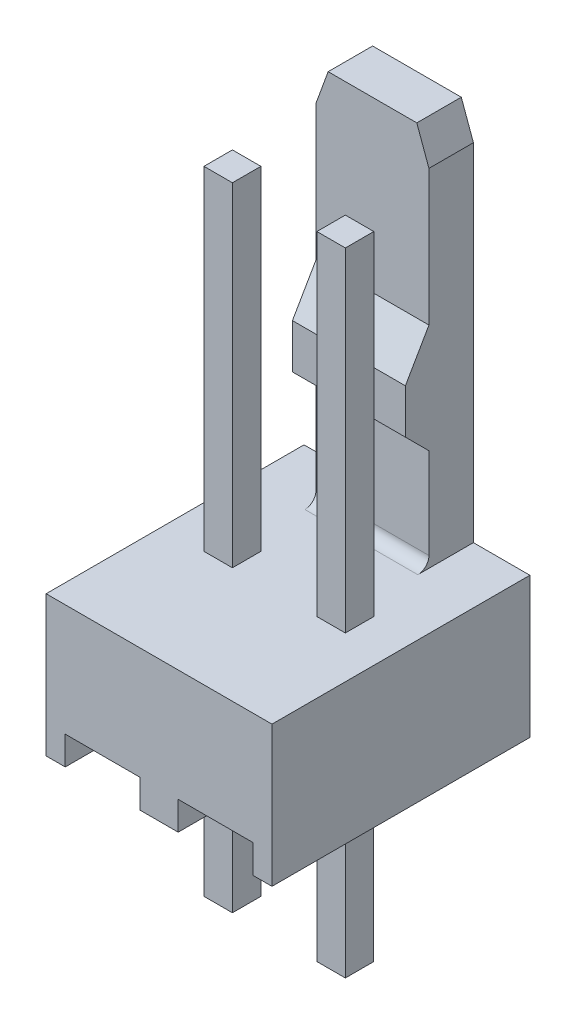
SolidWorks part; units mm, degrees
ref_plane "Front Plane" through (0, 0, 0) normal (0, 0, 1) x (1, 0, 0)
ref_plane "Top Plane" through (0, 0, 0) normal (0, 1, 0) x (1, 0, 0)
ref_plane "Right Plane" through (0, 0, 0) normal (1, 0, 0) x (0, 0, -1)
ref_plane "Plane1" through (0, -1.58, 0) normal (0, -1, 0) x (1, 0, 0)
sketch "Sketch1" plane through (0, -1.58, 0) normal (0, -1, 0) x (1, 0, 0)
  line L0 (2.54, -2.88) -> (2.54, 2.92)
  line L1 (2.54, 2.92) -> (-2.54, 2.92)
  line L2 (-2.54, 2.92) -> (-2.54, -2.88)
  line L3 (-2.54, -2.88) -> (2.54, -2.88)
extrude "Boss-Extrude1" add sketch "Sketch1" against normal blind 3.16
sketch "Sketch2" plane through (0, 1.58, 0) normal (0, 1, 0) x (-1, 0, 0)
  line L0 (1.27, -1.88) -> (1.27, -2.88)
  line L1 (1.27, -2.88) -> (-1.27, -2.88)
  line L2 (-1.27, -2.88) -> (-1.27, -1.88)
  line L3 (-1.27, -1.88) -> (1.27, -1.88)
extrude "Boss-Extrude2" add sketch "Sketch2" along normal blind 8.54
sketch "Sketch3" plane through (0, 0, -1.88) normal (0, 0, 1) x (1, 0, 0)
  line L0 (1.27, 10.12) -> (1.27, 3.87)
  line L1 (1.27, 3.87) -> (-1.27, 3.87)
  line L2 (-1.27, 3.87) -> (-1.27, 10.12)
  line L3 (-1.27, 10.12) -> (1.27, 10.12)
extrude "Boss-Extrude3" add sketch "Sketch3" along normal blind 0.53
sketch "Sketch4" plane through (0, 0, -2.88) normal (0, 0, -1) x (-1, 0, 0)
  line L0 (0.43, -1.58) -> (2.11, -1.58)
  line L1 (2.11, -1.58) -> (2.11, -0.94)
  line L2 (2.11, -0.94) -> (0.43, -0.94)
  line L3 (0.43, -0.94) -> (0.43, -1.58)
extrude "Cut-Extrude1" cut sketch "Sketch4" against normal through all
sketch "Sketch5" plane through (1.27, 0, 0) normal (1, 0, 0) x (0, 0, -1)
  line L0 (1.35, 6.318) -> (1.88, 6.318)
  line L1 (1.88, 6.318) -> (1.88, 10.12)
  line L2 (1.88, 10.12) -> (1.35, 10.12)
  line L3 (1.35, 10.12) -> (1.35, 6.318)
extrude "Cut-Extrude2" cut sketch "Sketch5" against normal through all
sketch "Sketch6" plane through (0, 0, -2.88) normal (0, 0, -1) x (-1, 0, 0)
  line L0 (-2.11, -1.58) -> (-0.43, -1.58)
  line L1 (-0.43, -1.58) -> (-0.43, -0.94)
  line L2 (-0.43, -0.94) -> (-2.11, -0.94)
  line L3 (-2.11, -0.94) -> (-2.11, -1.58)
extrude "Cut-Extrude3" cut sketch "Sketch6" against normal through all
sketch "Sketch7" plane through (0, -0.94, 0) normal (0, -1, 0) x (1, 0, 0)
  line L0 (-1.59, -0.32) -> (-1.59, 0.32)
  line L1 (-1.59, 0.32) -> (-0.95, 0.32)
  line L2 (-0.95, 0.32) -> (-0.95, -0.32)
  line L3 (-0.95, -0.32) -> (-1.59, -0.32)
extrude "Boss-Extrude4" add sketch "Sketch7" along normal blind 4.2
sketch "Sketch8" plane through (0, -0.94, 0) normal (0, -1, 0) x (1, 0, 0)
  line L0 (1.59, 0.32) -> (1.59, -0.315)
  line L1 (1.59, -0.315) -> (0.95, -0.315)
  line L2 (0.95, -0.315) -> (0.95, 0.32)
  line L3 (0.95, 0.32) -> (1.59, 0.32)
extrude "Boss-Extrude5" add sketch "Sketch8" along normal blind 4.2
sketch "Sketch9" plane through (0, 1.58, 0) normal (0, 1, 0) x (-1, 0, 0)
  line L0 (-1.59, -0.32) -> (-1.59, 0.32)
  line L1 (-1.59, 0.32) -> (-0.95, 0.32)
  line L2 (-0.95, 0.32) -> (-0.95, -0.32)
  line L3 (-0.95, -0.32) -> (-1.59, -0.32)
extrude "Boss-Extrude6" add sketch "Sketch9" along normal blind 7.5
sketch "Sketch10" plane through (0, 1.58, 0) normal (0, 1, 0) x (-1, 0, 0)
  line L0 (1.59, 0.32) -> (1.59, -0.32)
  line L1 (1.59, -0.32) -> (0.95, -0.32)
  line L2 (0.95, -0.32) -> (0.95, 0.32)
  line L3 (0.95, 0.32) -> (1.59, 0.32)
extrude "Boss-Extrude7" add sketch "Sketch10" along normal blind 7.5
draft "Draft1" type of draft neutral plane draft angle 45 faces to draft 1 face at (0, 3.87, -1.615) neutral plane through (1.27, 10.12, -1.88) neutral plane normal (0, 0, 1) parameters "D1"=45
draft "Draft2" type of draft neutral plane draft angle 60 faces to draft 1 face at (0, 6.318, -1.615) neutral plane through (-2.54, 6.318, -1.88) neutral plane normal (0, 0, 1) parameters "D1"=60
chamfer "Chamfer1" distance 0.75 angle 20 1 edges at (1.27, 10.12, -2.38)
chamfer "Chamfer2" distance 0.273 angle 70 1 edges at (-1.27, 10.12, -2.38)
fillet "Fillet1" radius 0.25 1 edges at (0, 1.58, -1.88)
sketch "Sketch11" plane through (0, -5.14, 0) normal (0, -1, 0) x (1, 0, 0)
  line L0 (-1.59, 0.32) -> (-0.95, -0.32) construction
  point P4 (-1.27, 0)
ref_plane "Plane2" through (0, 0, 0) normal (0, 0, 1) x (1, 0, 0)
sketch "Sketch12" plane through (0, 0, 0) normal (0, 0, 1) x (1, 0, 0)
  line L0 (-1.27, -5.14) -> (-1.27, -7.0331) construction
  line L1 (-1.59, -5.14) -> (-0.95, -5.14) construction
